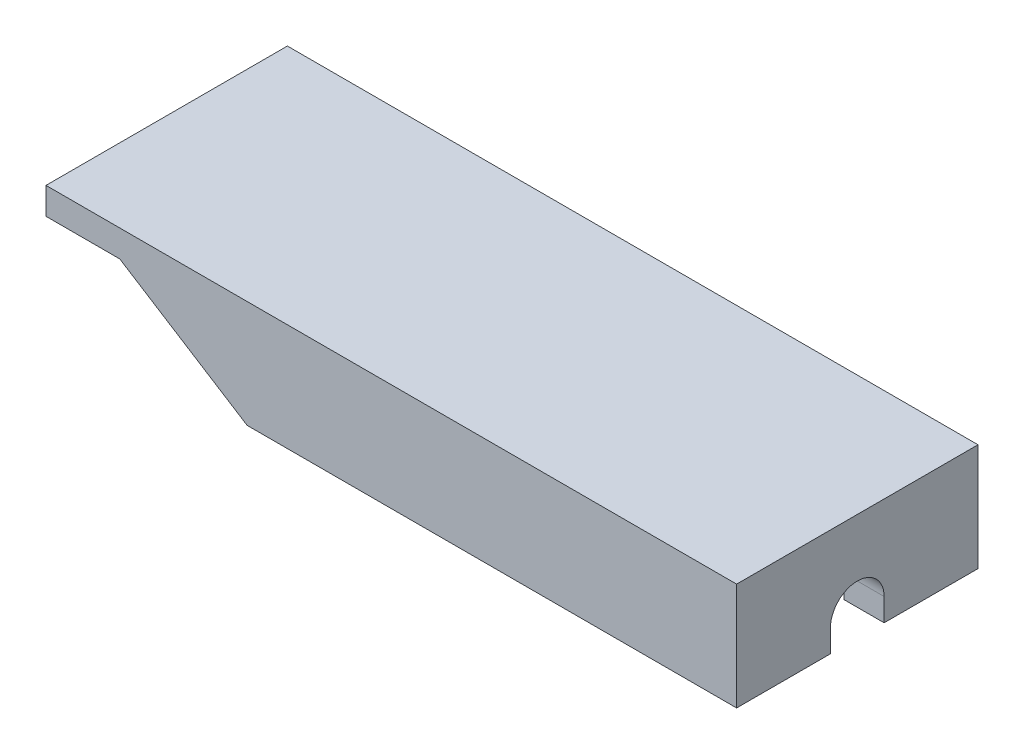
SolidWorks part; units mm, degrees
ref_plane "前视基准面" through (0, 0, 0) normal (0, 0, 1) x (1, 0, 0)
ref_plane "上视基准面" through (0, 0, 0) normal (0, 1, 0) x (1, 0, 0)
ref_plane "右视基准面" through (0, 0, 0) normal (1, 0, 0) x (0, 0, -1)
sketch "草图1" plane through (0, 0, 0) normal (0, 0, 1) x (1, 0, 0)
  line L0 (0, 0) -> (51.5, 0)
  line L1 (51.5, 0) -> (51.5, -8)
  line L4 (51.5, -8) -> (15, -8)
  line L5 (15, -8) -> (5.5, -2)
  line L6 (5.5, -2) -> (0, -2)
  line L7 (0, -2) -> (0, 0)
  point P5 (0, 0)
  dimension "D1" = 2
  dimension "D2" = 51.5
  dimension "D3" = 5.5
  dimension "D4" = 9.5
  dimension "D5" = 6
extrude "凸台-拉伸1" add sketch "草图1" along normal mid plane 18
sketch "草图2" plane through (0, -8, 0) normal (0, -1, 0) x (1, 0, 0)
  line L75 (15, -6) -> (48.5, -6)
  line L76 (5.5, -6) -> (15, -6)
  line L77 (3, -6) -> (5.5, -6)
  line L78 (3, 6) -> (3, -6)
  line L79 (5.5, 6) -> (3, 6)
  line L80 (15, 6) -> (5.5, 6)
  line L81 (48.5, 6) -> (15, 6)
  line L82 (48.5, -6) -> (48.5, 6)
  line L83 (15, -6) -> (48.5, -6)
  line L84 (5.5, -6) -> (15, -6)
  line L85 (3, -6) -> (5.5, -6)
  line L86 (3, 6) -> (3, -6)
  line L87 (5.5, 6) -> (3, 6)
  line L88 (15, 6) -> (5.5, 6)
  line L89 (48.5, 6) -> (15, 6)
  line L90 (48.5, -6) -> (48.5, 6)
  dimension "D1" = 3
extrude "切除-拉伸1" cut sketch "草图2" against normal offset from surface (5 mm away) 3 up to face at (25.75, 0, 0)
sketch "草图3" plane through (51.5, 0, 0) normal (1, 0, 0) x (0, 0, -1)
  line L5 (0, 0) -> (0, -8) construction
  line L6 (-9, 0) -> (9, 0) construction
  line L7 (-9, -8) -> (9, -8) construction
  line L8 (2, -6.3) -> (2, -8)
  line L9 (2, -8) -> (-2, -8)
  line L10 (-2, -8) -> (-2, -6.3)
  arc A1 (-2, -6.3) -> (2, -6.3) centre (0, -6.3) cw
  point P8 (0, 0)
  dimension "D1" = 1.7
  dimension "D2" = 2
extrude "切除-拉伸2" cut sketch "草图3" against normal up to next
